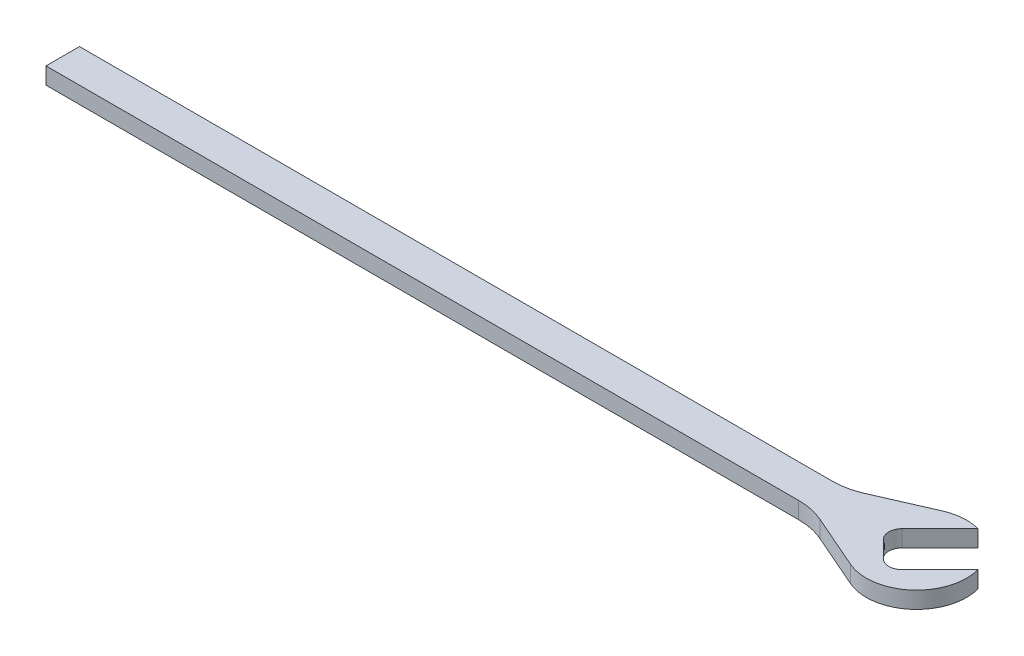
SolidWorks part; units mm, degrees
ref_plane "Front Plane" through (0, 0, 0) normal (0, 0, 1) x (1, 0, 0)
ref_plane "Top Plane" through (0, 0, 0) normal (0, 1, 0) x (1, 0, 0)
ref_plane "Right Plane" through (0, 0, 0) normal (1, 0, 0) x (0, 0, -1)
sketch "Sketch1" plane through (0, 0, 0) normal (0, 1, 0) x (1, 0, 0)
  line L0 (1.2595, 2.5863) -> (-100.3405, 2.5863)
  line L1 (-100.3405, 2.5863) -> (-103.395, 2.5863)
  line L2 (-103.395, 2.5863) -> (-103.395, -3.7637)
  line L3 (-103.395, -3.7637) -> (39.3595, -3.7637)
  line L4 (44.447, -4.8272) -> (54.7144, -9.3161)
  line L5 (67.7304, 1.8765) -> (60.5462, -5.3077)
  line L6 (56.9541, -5.3077) -> (53.811, -2.1646)
  line L7 (53.811, 1.4275) -> (60.9952, 8.6117)
  line L8 (54.7144, 8.1386) -> (44.447, 3.6498)
  line L9 (39.3595, 2.5863) -> (1.2595, 2.5863)
  arc A0 (60.9952, 8.6117) -> (58.53, 8.9363) centre (58.53, -0.5887) ccw
  arc A1 (58.53, 8.9363) -> (54.7144, 8.1386) centre (58.53, -0.5887) ccw
  spline S0 degree 2 poles (39.3595, -3.7637) (40.6725, -3.7637) (41.9582, -4.0325) (43.2434, -4.3011) (44.447, -4.8272) knots 0 0 0 0.5 0.5 1 1 1
  spline S1 degree 2 poles (54.7144, -9.3161) (55.9467, -9.8549) (57.2805, -10.0314) (58.6135, -10.2079) (59.9443, -10.0082) (61.274, -9.8086) (62.4974, -9.2481) (63.7199, -8.6881) (64.7403, -7.8108) (65.7598, -6.9341) (66.4974, -5.8085) (67.2343, -4.6838) (67.6313, -3.398) (68.0279, -2.1132) (68.0533, -0.7677) (68.0786, 0.5769) (67.7304, 1.8765) knots 0 0 0 0.125 0.125 0.25 0.25 0.375 0.375 0.5 0.5 0.625 0.625 0.75 0.75 0.875 0.875 1 1 1
  spline S2 degree 2 poles (60.5462, -5.3077) (60.1892, -5.6647) (59.7222, -5.8583) (59.2559, -6.0515) (58.7502, -6.0516) (58.2455, -6.0517) (57.7781, -5.8583) (57.3116, -5.6651) (56.9541, -5.3077) knots 0 0 0 0.25 0.25 0.5 0.5 0.75 0.75 1 1 1
  spline S3 degree 2 poles (53.811, -2.1646) (53.454, -1.8075) (53.2604, -1.3406) (53.0672, -0.8743) (53.0671, -0.3685) (53.067, 0.1361) (53.2604, 0.6035) (53.4536, 1.07) (53.811, 1.4275) knots 0 0 0 0.25 0.25 0.5 0.5 0.75 0.75 1 1 1
  spline S4 degree 2 poles (44.447, 3.6498) (43.2439, 3.1238) (41.9582, 2.855) (40.6731, 2.5863) (39.3595, 2.5863) knots 0 0 0 0.5 0.5 1 1 1
  point P19 (0, 0)
extrude "Boss-Extrude1" add sketch "Sketch1" along normal blind 3.175
